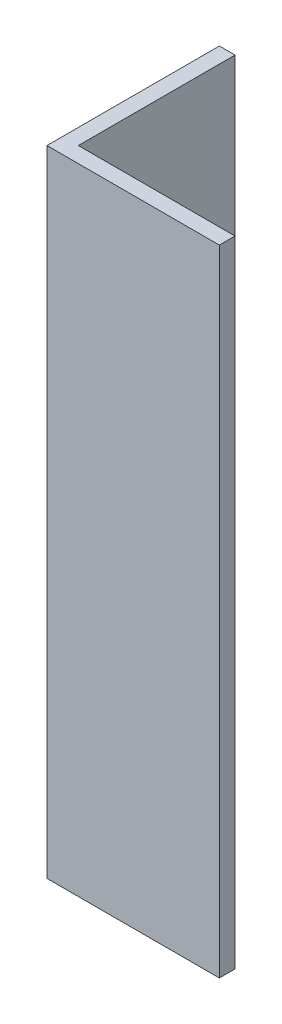
SolidWorks part; units mm, degrees
ref_plane "Спереди" through (0, 0, 0) normal (0, 0, 1) x (1, 0, 0)
ref_plane "Сверху" through (0, 0, 0) normal (0, 1, 0) x (1, 0, 0)
ref_plane "Справа" through (0, 0, 0) normal (1, 0, 0) x (0, 0, -1)
sketch "Эскиз1" plane through (0, 0, 0) normal (0, 1, 0) x (1, 0, 0)
  line L0 (0, -1.0719) -> (0, -21.0719)
  line L1 (0, -21.0719) -> (20, -21.0719)
  line L2 (20, -21.0719) -> (20, -23.0719)
  line L3 (20, -23.0719) -> (-2, -23.0719)
  line L4 (-2, -23.0719) -> (-2, -1.0719)
  line L5 (-2, -1.0719) -> (0, -1.0719)
extrude "Вытянуть1" add sketch "Эскиз1" along normal blind 81
